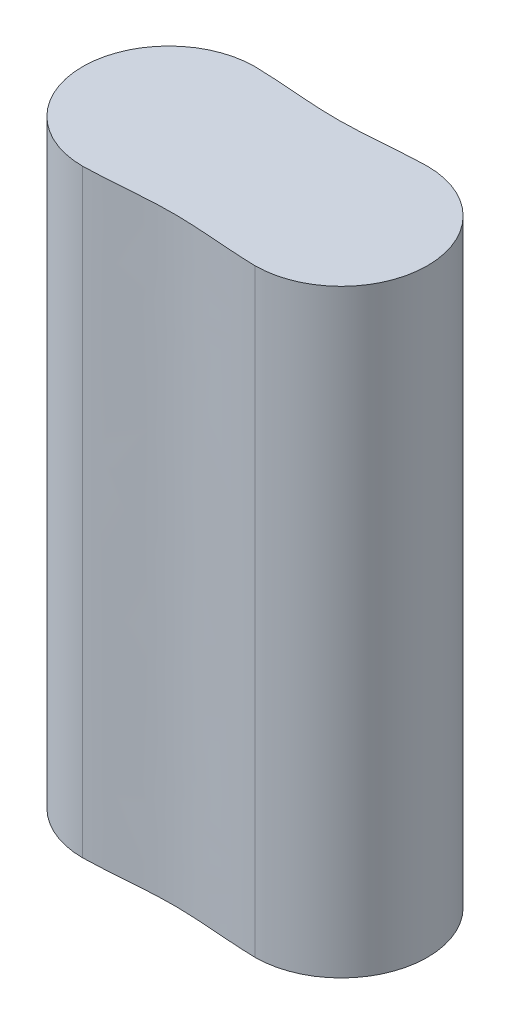
SolidWorks part; units mm, degrees
ref_plane "Front Plane" through (0, 0, 0) normal (0, 0, 1) x (1, 0, 0)
ref_plane "Top Plane" through (0, 0, 0) normal (0, 1, 0) x (1, 0, 0)
ref_plane "Right Plane" through (0, 0, 0) normal (1, 0, 0) x (0, 0, -1)
sketch "Sketch1" plane through (0, 0, 0) normal (0, 1, 0) x (1, 0, 0)
  line L0 (0, 0) -> (19, 0)
  line L1 (9.5, 0) -> (9.5, 9)
  circle A0 centre (0, 0) radius 9.5
  circle A1 centre (19, 0) radius 9.5
  spline S0 degree 3 poles (0, 9.5) (3.0981, 9.4381) (9.5, 8.5619) (15.9019, 9.4381) (19, 9.5) knots 0.292289 0.292289 0.292289 0.292289 0.5 0.707711 0.707711 0.707711 0.707711
  spline S1 degree 3 poles (0, -9.5) (3.0981, -9.4381) (9.5, -8.5619) (15.9019, -9.4381) (19, -9.5) knots 0.292289 0.292289 0.292289 0.292289 0.5 0.707711 0.707711 0.707711 0.707711
  dimension "D1" = 19
  dimension "D2" = 19
extrude "Boss-Extrude1" add sketch "Sketch1" along normal blind 66
